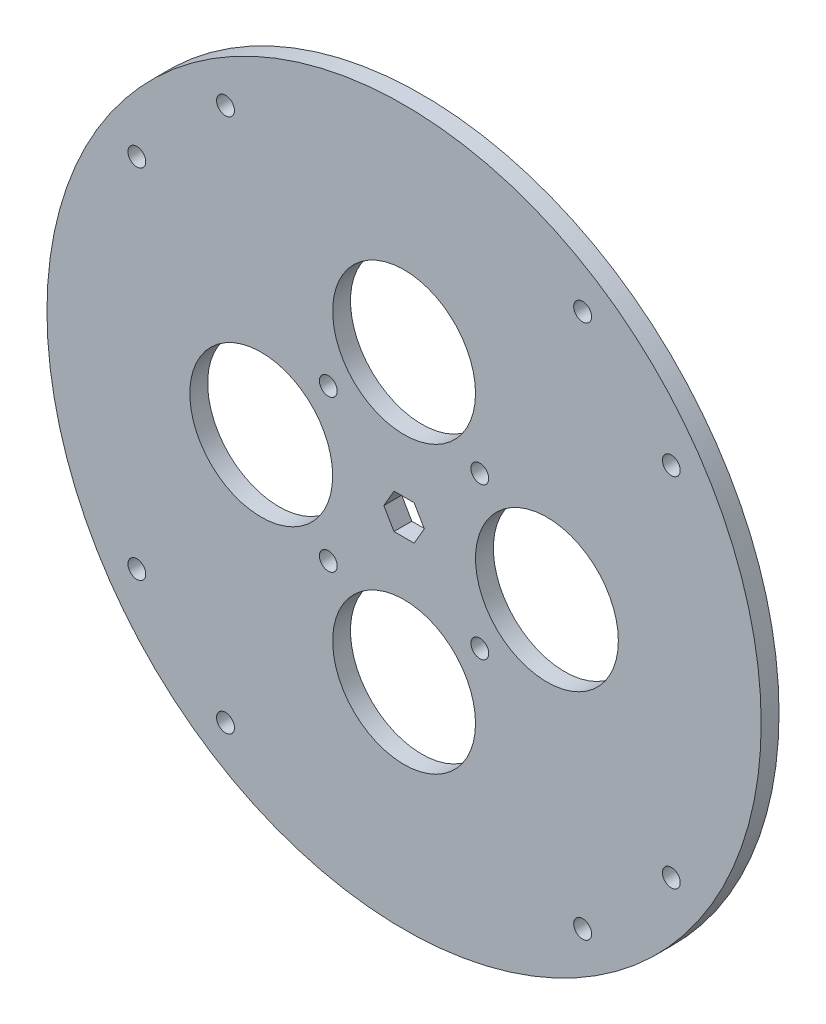
SolidWorks part; units mm, degrees
ref_plane "Front Plane" through (0, 0, 0) normal (0, 0, 1) x (1, 0, 0)
ref_plane "Top Plane" through (0, 0, 0) normal (0, 1, 0) x (1, 0, 0)
ref_plane "Right Plane" through (0, 0, 0) normal (1, 0, 0) x (0, 0, -1)
sketch "Sketch1" plane through (0, 0, 0) normal (0, 0, 1) x (1, 0, 0)
  line L1 (7.1857, 0) -> (3.5929, 6.223)
  line L2 (3.5929, 6.223) -> (-3.5929, 6.223)
  line L3 (-3.5929, 6.223) -> (-7.1857, 0)
  line L4 (-7.1857, 0) -> (-3.5929, -6.223)
  line L5 (-3.5929, -6.223) -> (3.5929, -6.223)
  line L6 (3.5929, -6.223) -> (7.1857, 0)
  circle A0 centre (0, 0) radius 127
  circle A2 centre (0, 50.8) radius 25.4
  circle A3 centre (50.8, 0) radius 25.4
  circle A4 centre (0, -50.8) radius 25.4
  circle A5 centre (-50.8, 0) radius 25.4
  circle A7 centre (0, 0) radius 203.2 construction
  circle A8 centre (0, 0) radius 6.223 construction
  point P14 (0, 0)
  dimension "D1" = 254
  dimension "D2" = 25.4
  dimension "D3" = 4
  dimension "2" = 50.8
  dimension "D4" = 12.446
  dimension "D5" = 406.4
extrude "Boss-Extrude1" add sketch "Sketch1" along normal blind 6.35
sketch "Sketch3" plane through (0, 0, 0) normal (0, 0, -1) x (-1, 0, 0)
  line L0 (-26.9408, -26.9408) -> (26.9408, 26.9408) construction
  line L1 (-26.9408, 26.9408) -> (26.9408, -26.9408) construction
  line L2 (-63.5, 95.0381) -> (0, 0) construction
  line L3 (0, 0) -> (63.5, 95.0381) construction
  circle A0 centre (-26.9408, 26.9408) radius 3.175
  circle A1 centre (26.9408, 26.9408) radius 3.175
  circle A2 centre (26.9408, -26.9408) radius 3.175
  circle A3 centre (-26.9408, -26.9408) radius 3.175
  circle A4 centre (-63.5, 95.0381) radius 3.175
  circle A5 centre (63.5, 95.0381) radius 3.175
  circle A6 centre (95.0381, 63.5) radius 3.175
  circle A7 centre (95.0381, -63.5) radius 3.175
  circle A8 centre (63.5, -95.0381) radius 3.175
  circle A9 centre (-63.5, -95.0381) radius 3.175
  circle A10 centre (-95.0381, -63.5) radius 3.175
  circle A11 centre (-95.0381, 63.5) radius 3.175
  point P11 (0, 0)
  point P29 (0, 0)
  dimension "D1" = 6.35
  dimension "D2" = 76.2
  dimension "D3" = 127
  dimension "D4" = 114.3
  dimension "D5" = 4
extrude "Cut-Extrude1" cut sketch "Sketch3" against normal blind 6.35
